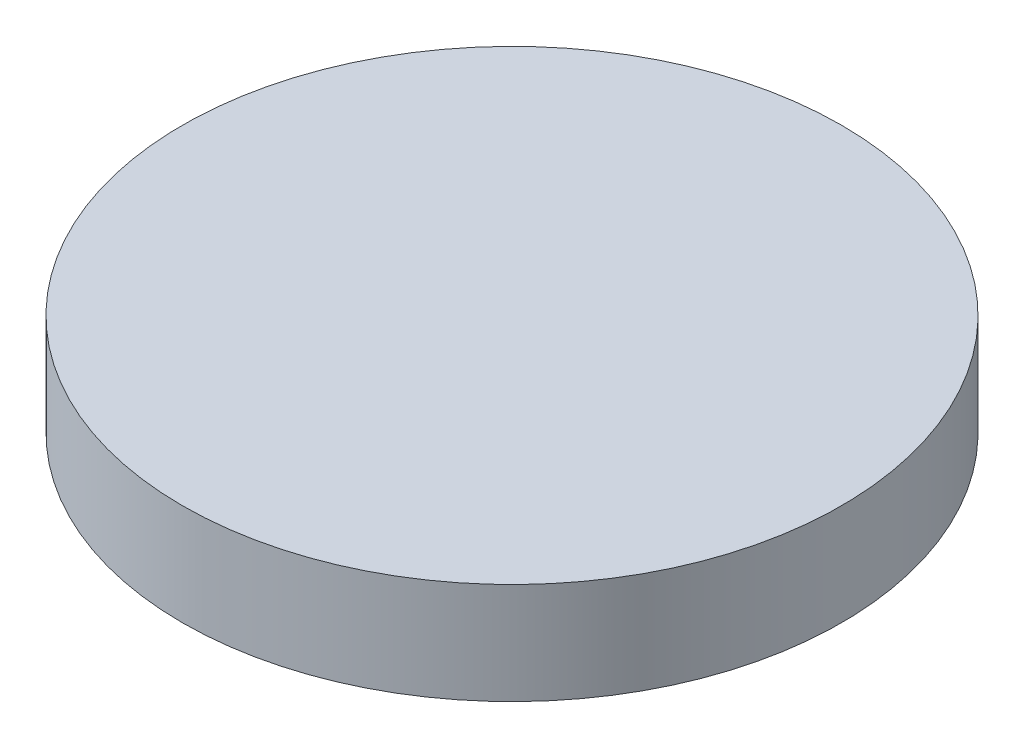
SolidWorks part; units mm, degrees
ref_plane "Plano frontal" through (0, 0, 0) normal (0, 0, 1) x (1, 0, 0)
ref_plane "Plano superior" through (0, 0, 0) normal (0, 1, 0) x (1, 0, 0)
ref_plane "Plano direito" through (0, 0, 0) normal (1, 0, 0) x (0, 0, -1)
sketch "Esboço1" plane through (0, 0, 0) normal (0, 1, 0) x (1, 0, 0)
  circle A0 centre (0, 0) radius 32.5
  dimension "D1" = 65
extrude "Ressalto-extrusão1" add sketch "Esboço1" along normal blind 10
